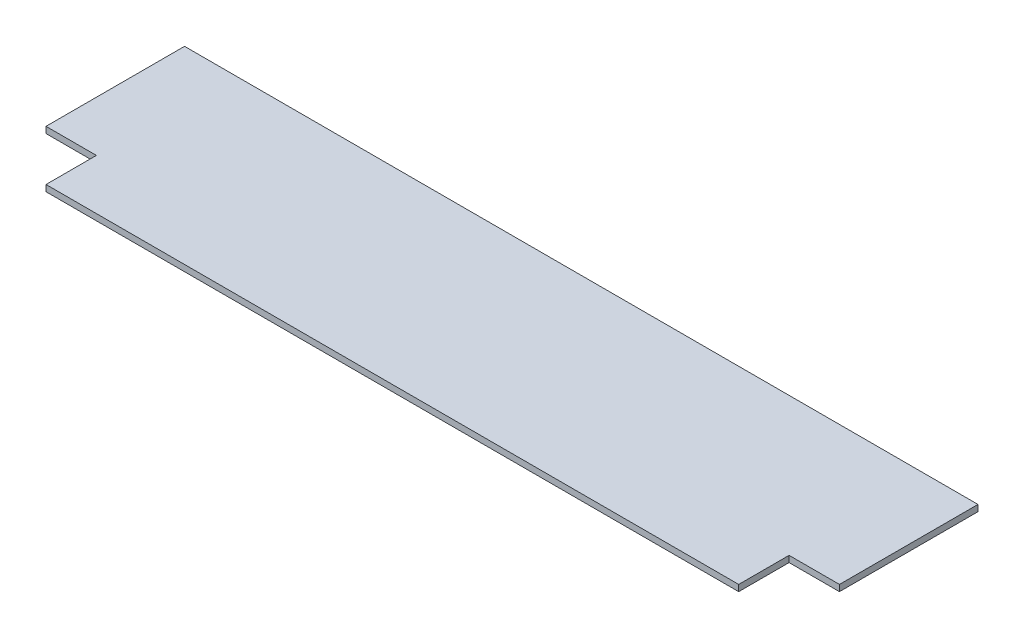
SolidWorks part; units mm, degrees
ref_plane "Front Plane" through (0, 0, 0) normal (0, 0, 1) x (1, 0, 0)
ref_plane "Top Plane" through (0, 0, 0) normal (0, 1, 0) x (1, 0, 0)
ref_plane "Right Plane" through (0, 0, 0) normal (1, 0, 0) x (0, 0, -1)
sketch "Sketch1" plane through (0, 0, 0) normal (0, 1, 0) x (1, 0, 0)
  line L1 (-400.05, -95.25) -> (400.05, -95.25)
  line L2 (-400.05, -95.25) -> (-400.05, 95.25)
  line L3 (-400.05, 95.25) -> (400.05, 95.25)
  line L4 (400.05, -95.25) -> (400.05, 95.25)
  line L5 (-400.05, -95.25) -> (400.05, 95.25) construction
  line L6 (-400.05, 95.25) -> (400.05, -95.25) construction
  point P0 (0, 0)
  dimension "D1" = 190.5
  dimension "D2" = 800.1
extrude "Boss-Extrude1" add sketch "Sketch1" along normal blind 6.35
sketch "Sketch2" plane through (0, 6.35, 0) normal (0, 1, 0) x (1, 0, 0)
  line L1 (400.05, -95.25) -> (349.25, -95.25)
  line L2 (400.05, -95.25) -> (400.05, -44.45)
  line L3 (400.05, -44.45) -> (349.25, -44.45)
  line L4 (349.25, -95.25) -> (349.25, -44.45)
  line L5 (-400.05, -95.25) -> (-349.25, -95.25)
  line L6 (-400.05, -95.25) -> (-400.05, -44.45)
  line L7 (-400.05, -44.45) -> (-349.25, -44.45)
  line L8 (-349.25, -95.25) -> (-349.25, -44.45)
  dimension "D1" = 50.8
  dimension "D2" = 50.8
  dimension "D3" = 50.8
  dimension "D4" = 50.8
extrude "Cut-Extrude1" cut sketch "Sketch2" against normal through all
